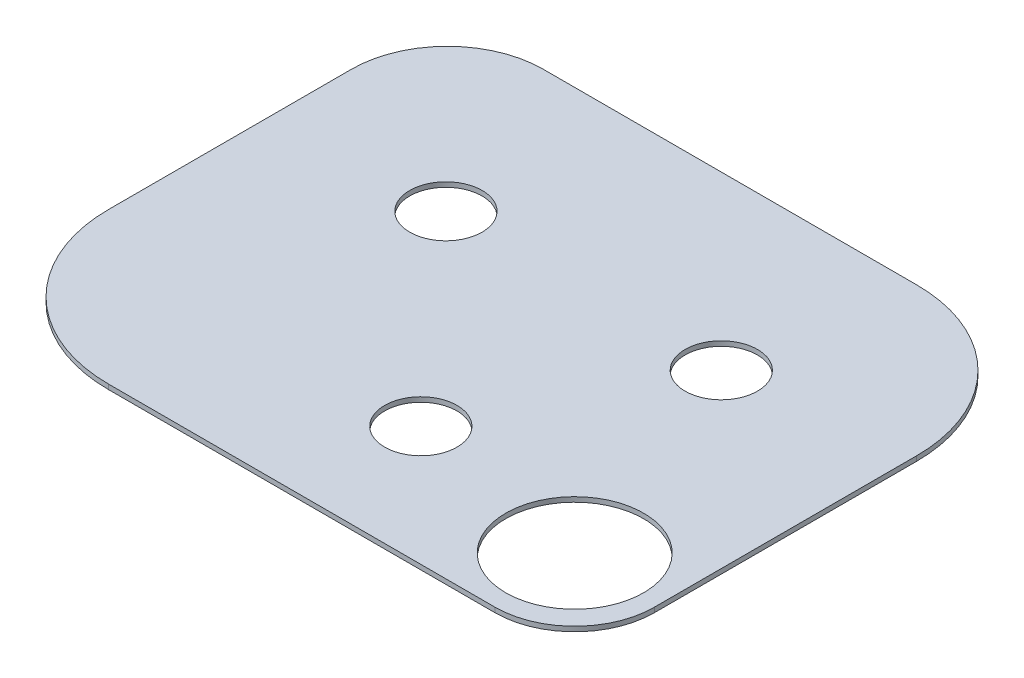
SolidWorks part; units mm, degrees
ref_plane "Front Plane" through (0, 0, 0) normal (0, 0, 1) x (1, 0, 0)
ref_plane "Top Plane" through (0, 0, 0) normal (0, 1, 0) x (1, 0, 0)
ref_plane "Right Plane" through (0, 0, 0) normal (1, 0, 0) x (0, 0, -1)
sketch "Sketch1" plane through (0, 0, 0) normal (0, 1, 0) x (1, 0, 0)
  line L1 (64, -50.8) -> (-64, -50.8)
  line L2 (64, -50.8) -> (64, 50.8)
  line L3 (64, 50.8) -> (-64, 50.8)
  line L4 (-64, -50.8) -> (-64, 50.8)
  line L5 (64, -50.8) -> (-64, 50.8) construction
  line L6 (64, 50.8) -> (-64, -50.8) construction
  point P0 (0, 0)
  dimension "D1" = 128
  dimension "D2" = 101.6
extrude "Boss-Extrude1" add sketch "Sketch1" along normal blind 1
sketch "Sketch2" plane through (0, 1, 0) normal (0, 1, 0) x (1, 0, 0)
  line L0 (-64, -50.8) -> (-64, -19.4224)
  line L1 (-64, 50.8) -> (-64, -50.8) construction
  line L2 (-64, -50.8) -> (-32.6224, -50.8)
  line L3 (-64, -50.8) -> (64, -50.8) construction
  line L4 (47.49, -50.8) -> (64, -50.8)
  line L5 (64, -50.8) -> (64, -34.29)
  line L6 (64, -50.8) -> (64, 50.8) construction
  line L7 (-64, 30.9236) -> (-64, 50.8)
  line L8 (-64, 50.8) -> (-44.1236, 50.8)
  line L9 (64, 50.8) -> (-64, 50.8) construction
  line L10 (64, 20.1165) -> (64, 50.8)
  line L11 (64, 50.8) -> (33.3165, 50.8)
  arc A0 (-32.6224, -50.8) -> (-64, -19.4224) centre (-32.6224, -19.4224) cw
  arc A1 (-64, 30.9236) -> (-44.1236, 50.8) centre (-44.1236, 30.9236) cw
  arc A2 (33.3165, 50.8) -> (64, 20.1165) centre (33.3165, 20.1165) cw
  arc A3 (64, -34.29) -> (47.49, -50.8) centre (47.49, -34.29) cw
  point P28 (34.1034, -50.8)
  point P29 (42.4712, -50.8)
  dimension "D1" = 16.51
  dimension "D2" = 30.6835
  dimension "D3" = 19.8764
  dimension "D4" = 31.3776
extrude "Cut-Extrude1" cut sketch "Sketch2" against normal blind 1
sketch "Sketch3" plane through (0, 1, 0) normal (0, 1, 0) x (1, 0, 0)
  line L1 (64, -34.29) -> (64, 20.1165) construction
  line L2 (46, -32.8) -> (64, -32.8) construction
  line L3 (46, -32.8) -> (46, -50.8) construction
  line L4 (-32.6224, -50.8) -> (47.49, -50.8) construction
  line L5 (7.3, -26) -> (7.3, -50.8) construction
  line L6 (-28.7, -50.8) -> (-28.7, 15.2) construction
  line L7 (-28.7, 15.2) -> (-64, 15.2) construction
  line L8 (-64, 30.9236) -> (-64, -19.4224) construction
  line L9 (64, 15.2) -> (28.4, 15.2) construction
  line L10 (28.4, 15.2) -> (28.4, 50.8) construction
  line L11 (33.3165, 50.8) -> (-44.1236, 50.8) construction
  line L12 (7.3, -26) -> (64, -26) construction
  circle A0 centre (46, -32.8) radius 14.3
  circle A1 centre (7.3, -26) radius 7.5
  circle A2 centre (-28.7, 15.2) radius 7.5
  circle A3 centre (28.4, 15.2) radius 7.5
  point P27 (0, 0)
  dimension "D1" = 28.6
  dimension "D4" = 15
  dimension "D2" = 18
  dimension "D3" = 24.8
  dimension "D5" = 56.7
  dimension "D6" = 35.6
  dimension "D7" = 35.6
  dimension "D8" = 35.6
  dimension "D9" = 92.7
extrude "Cut-Extrude2" cut sketch "Sketch3" against normal blind 1
